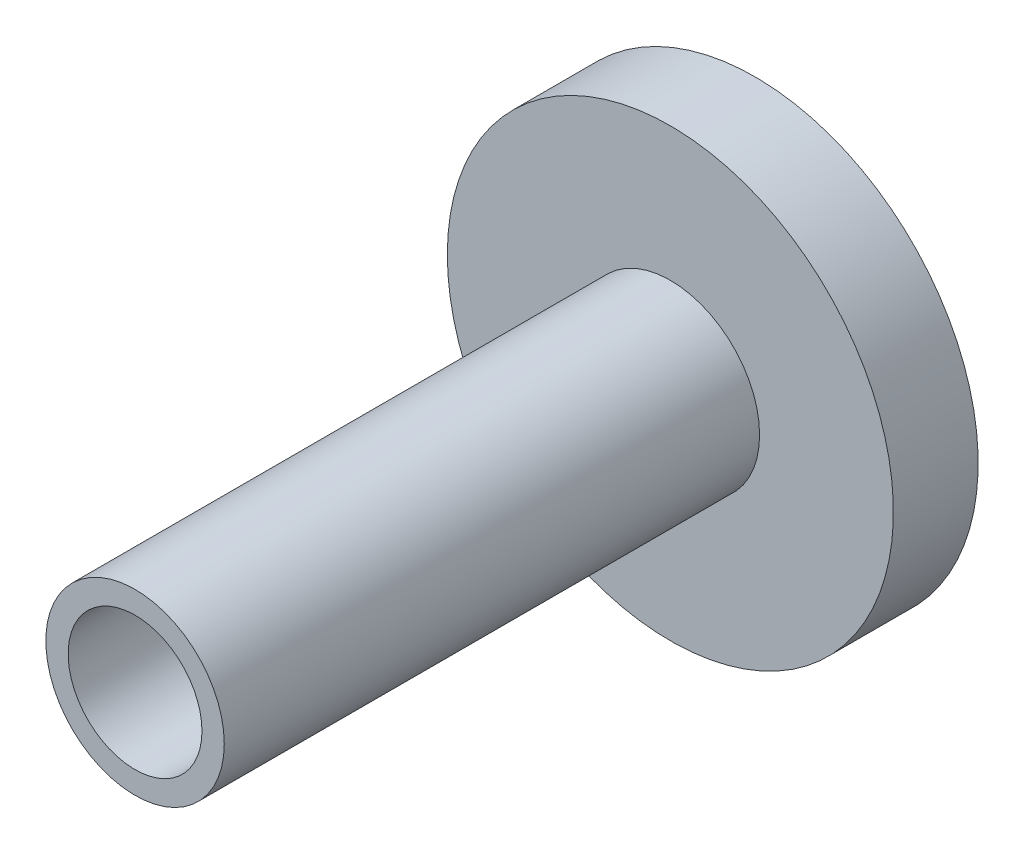
SolidWorks part; units mm, degrees
material "不锈钢 (铁素体)"
ref_plane "前视基准面" through (0, 0, 0) normal (0, 0, 1) x (1, 0, 0)
ref_plane "上视基准面" through (0, 0, 0) normal (0, 1, 0) x (1, 0, 0)
ref_plane "右视基准面" through (0, 0, 0) normal (1, 0, 0) x (0, 0, -1)
sketch "草图1" plane through (0, 0, 0) normal (0, 0, 1) x (1, 0, 0)
  circle A0 centre (0, 0) radius 5
  dimension "D1" = 10
extrude "凸台-拉伸1" add sketch "草图1" along normal blind 1.9
sketch "草图2" plane through (0, 0, 1.9) normal (0, 0, 1) x (1, 0, 0)
  circle A0 centre (0, 0) radius 2
  dimension "D1" = 4
extrude "凸台-拉伸2" add sketch "草图2" along normal blind 12
sketch "草图3" plane through (0, 0, 13.9) normal (0, 0, 1) x (1, 0, 0)
  circle A0 centre (0, 0) radius 1.5
  dimension "D1" = 3
extrude "切除-拉伸1" cut sketch "草图3" against normal blind 12
cosmetic thread "装饰螺纹线1" parameters "D2"=3.6
